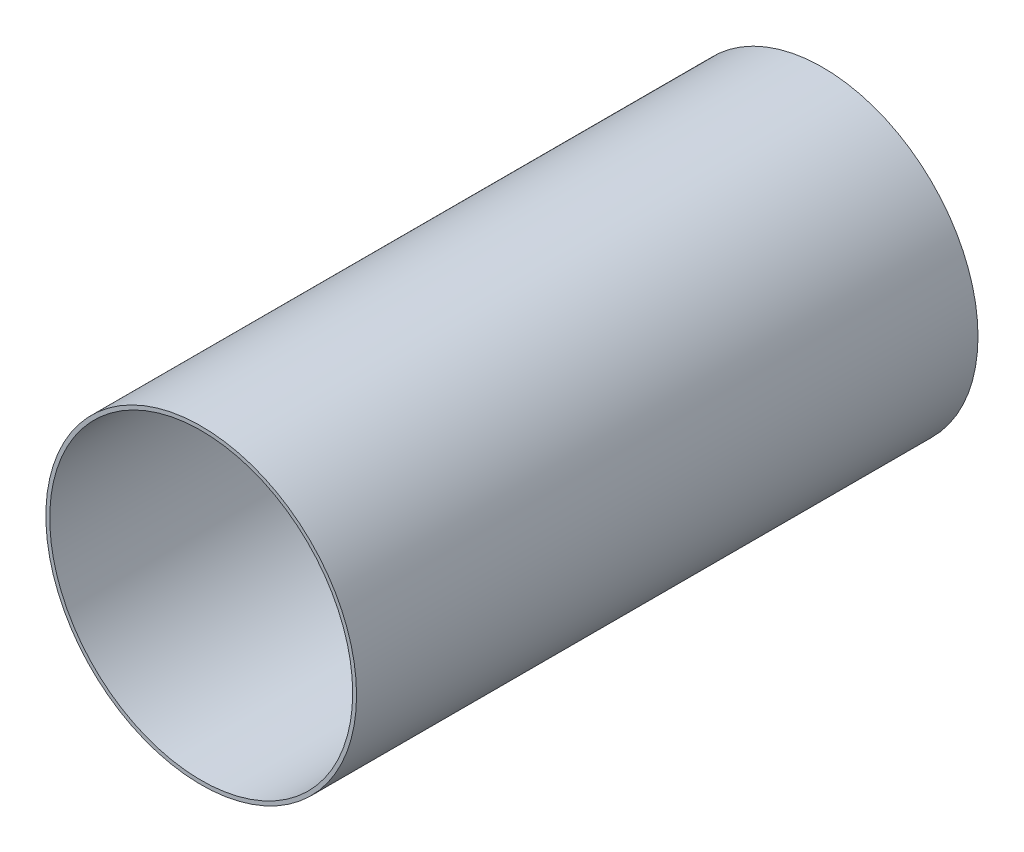
SolidWorks part; units mm, degrees
ref_plane "Front Plane" through (0, 0, 0) normal (0, 0, 1) x (1, 0, 0)
ref_plane "Top Plane" through (0, 0, 0) normal (0, 1, 0) x (1, 0, 0)
ref_plane "Right Plane" through (0, 0, 0) normal (1, 0, 0) x (0, 0, -1)
sketch "Sketch1" plane through (0, 0, 0) normal (0, 0, 1) x (1, 0, 0)
  circle A0 centre (0, 0) radius 40
  circle A1 centre (0, 0) radius 39
  dimension "D1" = 80
  dimension "D2" = 1
extrude "Boss-Extrude1" add sketch "Sketch1" along normal blind 160
